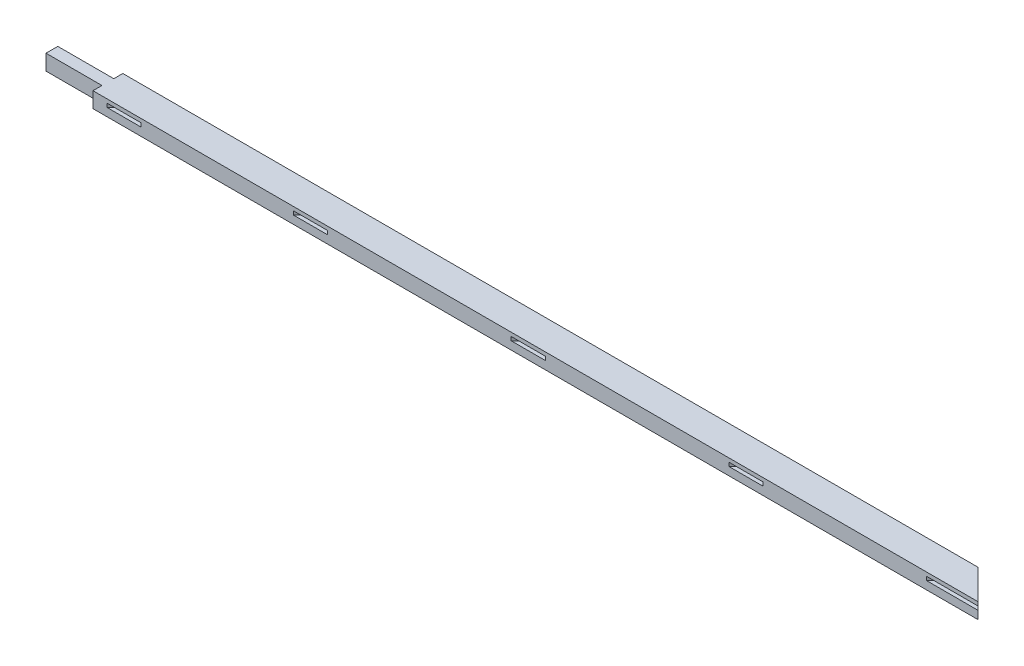
SolidWorks part; units mm, degrees
ref_plane "前视基准面" through (0, 0, 0) normal (0, 0, 1) x (1, 0, 0)
ref_plane "上视基准面" through (0, 0, 0) normal (0, 1, 0) x (1, 0, 0)
ref_plane "右视基准面" through (0, 0, 0) normal (1, 0, 0) x (0, 0, -1)
sketch "草图1" plane through (0, 0, 0) normal (0, 1, 0) x (1, 0, 0)
  line L0 (0, 0) -> (0, -9.5)
  line L1 (0, -9.5) -> (90, -9.5)
  line L2 (90, -9.5) -> (90, -24)
  line L3 (90, -24) -> (1513, -24)
  line L4 (1513, -24) -> (1465, 24)
  line L5 (1465, 24) -> (90, 24)
  line L6 (90, 24) -> (90, 9.5)
  line L7 (90, 9.5) -> (0, 9.5)
  line L8 (0, 9.5) -> (0, 0)
  line L9 (0, 0) -> (-29.7495, 0) construction
  dimension "D1" = 19
  dimension "D2" = 48
  dimension "D3" = 1513
  dimension "D4" = 1465
  dimension "D5" = 90
extrude "凸台-拉伸1" add sketch "草图1" along normal blind 25
sketch "草图2" plane through (0, 25, 0) normal (0, 1, 0) x (1, 0, 0)
  line L0 (112.5, 24) -> (120, 16.5)
  line L1 (1465, 24) -> (90, 24) construction
  line L2 (120, 16.5) -> (160, 16.5)
  line L3 (160, 16.5) -> (167.5, 24)
  line L4 (167.5, 24) -> (112.5, 24)
  line L5 (140, 16.5) -> (140, 46.7248) construction
  dimension "D1" = 90
  dimension "D2" = 7.5
  dimension "D3" = 40
  dimension "D4" = 140
extrude "切除-拉伸1" cut sketch "草图2" against normal blind 6 from offset 6 offset against normal yes
pattern_linear "阵列(线性)1" count 2 spacing 300 along (1, 0, 0) of "切除-拉伸1"
pattern_linear "阵列(线性)3" count 3 spacing 350 along (1, 0, 0) of "阵列(线性)1"
mirror "镜向3" about plane through (0, 0, 0) normal (0, 0, 1) of "切除-拉伸1"
mirror "镜向5" about plane through (0, 0, 0) normal (0, 0, 1) of "阵列(线性)3", "阵列(线性)1"
sketch "草图3" plane through (0, 25, 0) normal (0, 1, 0) x (1, 0, 0)
  line L0 (1430.5, 24) -> (1438, 16.5)
  line L1 (1465, 24) -> (90, 24) construction
  line L2 (1438, 16.5) -> (1472.5, 16.5)
  line L3 (1513, -24) -> (1465, 24) construction
  line L4 (1472.5, 16.5) -> (1465, 24)
  line L5 (1465, 24) -> (1430.5, 24)
  dimension "D1" = 7.5
  dimension "D2" = 45
  dimension "D3" = 27
extrude "切除-拉伸3" cut sketch "草图3" against normal blind 6 from offset 6 offset against normal yes
sketch "草图4" plane through (0, 25, 0) normal (0, 1, 0) x (1, 0, 0)
  line L0 (1430.5, -24) -> (1438, -16.5)
  line L1 (90, -24) -> (1513, -24) construction
  line L2 (1438, -16.5) -> (1505.5, -16.5)
  line L3 (1513, -24) -> (1465, 24) construction
  line L4 (1505.5, -16.5) -> (1513, -24)
  line L5 (1513, -24) -> (1430.5, -24)
  dimension "D1" = 45
  dimension "D2" = 7.5
  dimension "D3" = 75
extrude "切除-拉伸4" cut sketch "草图4" against normal blind 6 from offset 6
